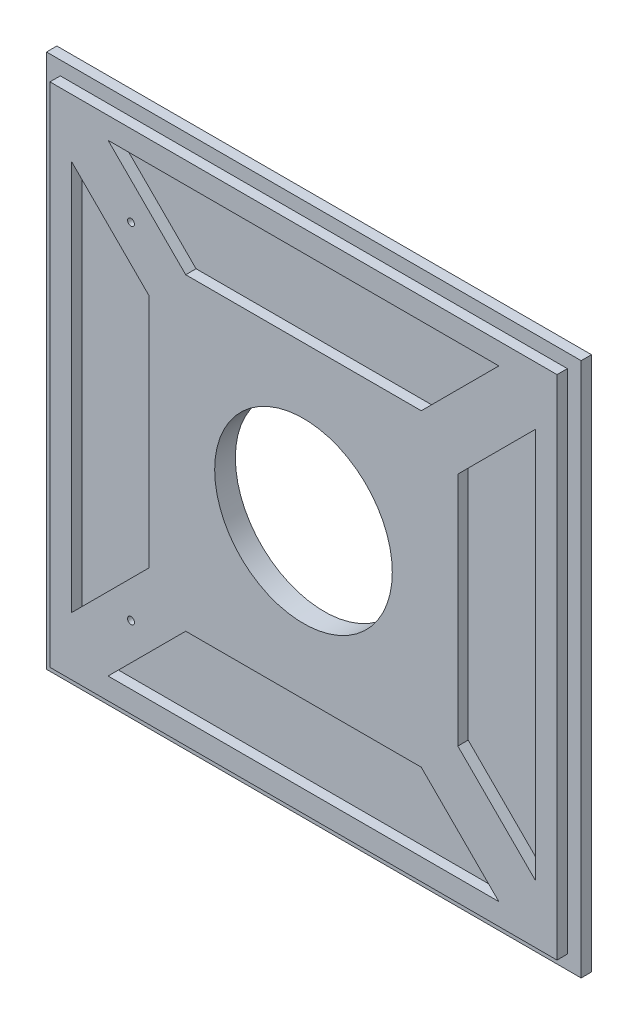
SolidWorks part; units mm, degrees
ref_plane "Front Plane" through (0, 0, 0) normal (0, 0, 1) x (1, 0, 0)
ref_plane "Top Plane" through (0, 0, 0) normal (0, 1, 0) x (1, 0, 0)
ref_plane "Right Plane" through (0, 0, 0) normal (1, 0, 0) x (0, 0, -1)
sketch "Sketch1" plane through (0, 0, 0) normal (0, 0, 1) x (1, 0, 0)
  line L1 (0, 0) -> (310, 0)
  line L2 (0, 0) -> (0, -310)
  line L3 (0, -310) -> (310, -310)
  line L4 (310, 0) -> (310, -310)
  dimension "D1" = 310
  dimension "D2" = 310
extrude "Boss-Extrude1" add sketch "Sketch1" along normal blind 6
sketch "Sketch3" plane through (0, 0, 6) normal (0, 0, 1) x (1, 0, 0)
  line L0 (0, 0) -> (310, -310) construction
  line L1 (302, -8) -> (302, -33)
  line L2 (310, 0) -> (0, -310) construction
  line L3 (302, -8) -> (277, -8)
  line L4 (8, -8) -> (8, -33)
  line L5 (8, -8) -> (33, -8)
  line L6 (8, -302) -> (8, -277)
  line L7 (8, -302) -> (33, -302)
  line L8 (302, -302) -> (277, -302)
  line L9 (302, -302) -> (302, -277)
  line L10 (0, 0) -> (0, -310) construction
  line L11 (268.2868, -20.5) -> (223.2868, -65.5)
  line L13 (20.5, -41.7132) -> (65.5, -86.7132)
  line L15 (41.7132, -289.5) -> (86.7132, -244.5)
  line L17 (289.5, -41.7132) -> (244.5, -86.7132)
  line L19 (33, -8) -> (277, -8)
  line L20 (268.2868, -20.5) -> (41.7132, -20.5)
  line L21 (8, -33) -> (8, -277)
  line L22 (20.5, -41.7132) -> (20.5, -268.2868)
  line L23 (302, -33) -> (302, -277)
  line L24 (289.5, -41.7132) -> (289.5, -268.2868)
  line L25 (33, -302) -> (277, -302)
  line L26 (268.2868, -289.5) -> (41.7132, -289.5)
  line L27 (86.7132, -65.5) -> (223.2868, -65.5)
  line L31 (244.5, -86.7132) -> (244.5, -223.2868)
  line L33 (86.7132, -244.5) -> (223.2868, -244.5)
  line L35 (65.5, -86.7132) -> (65.5, -223.2868)
  line L36 (86.7132, -65.5) -> (41.7132, -20.5)
  line L39 (244.5, -223.2868) -> (289.5, -268.2868)
  line L40 (223.2868, -244.5) -> (268.2868, -289.5)
  line L42 (65.5, -223.2868) -> (20.5, -268.2868)
  line L44 (310, 0) -> (0, 0) construction
  line L45 (310, -310) -> (310, 0) construction
  line L46 (0, -310) -> (310, -310) construction
  point P4 (135, -155)
  point P9 (175, -155)
  point P10 (155, -135)
  point P11 (155, -175)
  point P13 (155, -155)
  dimension "D1" = 25
  dimension "D2" = 25
  dimension "D3" = 25
  dimension "D4" = 25
  dimension "D5" = 25
  dimension "D6" = 25
  dimension "D7" = 25
  dimension "D8" = 25
  dimension "D9" = 8
  dimension "D10" = 45
  dimension "D11" = 12.5
  dimension "D12" = 12.5
  dimension "D13" = 12.5
  dimension "D14" = 12.5
  dimension "D15" = 20
  dimension "D16" = 20
  dimension "D17" = 20
  dimension "D18" = 20
  dimension "D19" = 45
  dimension "D20" = 45
  dimension "D21" = 45
  dimension "D22" = 15
  dimension "D23" = 15
  dimension "D24" = 15
  dimension "D25" = 15
  dimension "D26" = 15
  dimension "D27" = 15
  dimension "D28" = 15
  dimension "D29" = 15
  dimension "D30" = 8
  dimension "D31" = 8
  dimension "D32" = 8
extrude "Boss-Extrude2" add sketch "Sketch3" along normal blind 6
sketch "Sketch4" plane through (0, 0, 12) normal (0, 0, 1) x (1, 0, 0)
  line L0 (0, 0) -> (310, -310) construction
  line L1 (310, 0) -> (0, -310) construction
  circle A0 centre (155, -155) radius 51.5
  dimension "D1" = 103
extrude "Cut-Extrude1" cut sketch "Sketch4" against normal through all
sketch "Sketch10" plane through (0, 0, 0) normal (0, 0, -1) x (-1, 0, 0)
  line L0 (-310, -52.5) -> (0, -52.5)
  line L1 (-310, -310) -> (-310, 0) construction
  line L2 (0, 0) -> (0, -310) construction
  line L3 (-252.5, 0) -> (-252.5, -310)
  line L4 (-310, 0) -> (0, 0) construction
  line L5 (0, -310) -> (-310, -310) construction
  circle A0 centre (-252.5, -52.5) radius 10
  dimension "D3" = 20
  dimension "D1" = 57.5
  dimension "D2" = 52.5
extrude "corner cord hole" [suppressed] cut sketch "Sketch10" against normal through all contours A0
sketch "Sketch11" plane through (0, 0, 0) normal (0, 0, -1) x (-1, 0, 0)
  line L0 (-255, -55) -> (-55, -55) construction
  line L5 (-55, -55) -> (-55, -255) construction
  line L6 (-55, -255) -> (-255, -255) construction
  line L7 (-255, -255) -> (-255, -55) construction
  line L8 (-155, -103.5) -> (-155, -206.5) construction
  line L9 (-206.5, -155) -> (-103.5, -155) construction
  circle A0 centre (-155, -155) radius 51.5 construction
  circle A2 centre (-55, -55) radius 2
  circle A3 centre (-55, -255) radius 2
  point P11 (-155, -155)
  dimension "D6" = 4
  dimension "D7" = 4
  dimension "D1" = 200
  dimension "D2" = 200
  dimension "D3" = 100
  dimension "D4" = 100
extrude "Cut-Extrude5" cut sketch "Sketch11" against normal through all
sketch "Sketch12" plane through (0, 0, 0) normal (0, 0, -1) x (-1, 0, 0)
  line L0 (-339.9534, -155) -> (14.9572, -155) construction
  line L1 (-155, 5.3762) -> (-155, -332.8718) construction
  line L2 (0, 0) -> (0, -310) construction
  line L3 (-310, -310) -> (-310, 0) construction
  line L4 (-310, 0) -> (0, 0) construction
  line L5 (0, -310) -> (-310, -310) construction
  line L6 (-260, -155) -> (-260, -260) construction
  line L7 (-260, -260) -> (-50, -260) construction
  line L8 (-50, -260) -> (-50, -50) construction
  line L9 (-50, -50) -> (-260, -50) construction
  line L10 (-260, -50) -> (-260, -155) construction
  line L11 (-260, -110) -> (-285, -110) construction
  line L12 (-285, -110) -> (-285, -200) construction
  line L13 (-285, -200) -> (-260, -200) construction
  line L15 (-260, -99) -> (-285, -99)
  line L16 (-260, -99) -> (-260, -109)
  line L17 (-260, -109) -> (-285, -109)
  line L18 (-285, -99) -> (-285, -109)
  line L19 (-260, -211) -> (-285, -211)
  line L20 (-260, -211) -> (-260, -201)
  line L21 (-260, -201) -> (-285, -201)
  line L22 (-285, -211) -> (-285, -201)
  dimension "D1" = 105
  dimension "D2" = 105
  dimension "D3" = 210
  dimension "D4" = 210
  dimension "D5" = 25
  dimension "D6" = 105
  dimension "D7" = 90
  dimension "D8" = 60
  dimension "D9" = 1
  dimension "D10" = 1
  dimension "D11" = 10
  dimension "D12" = 10
  dimension "D13" = 25
  dimension "D14" = 25
extrude "Boss-Extrude3" add sketch "Sketch12" along normal blind 6.5
sketch "Sketch13" plane through (0, 0, -6.5) normal (0, 0, -1) x (-1, 0, 0)
  line L1 (-285, -99) -> (-260, -99)
  line L2 (-285, -99) -> (-285, -211)
  line L3 (-285, -211) -> (-260, -211)
  line L4 (-260, -99) -> (-260, -211)
extrude "Boss-Extrude4" add sketch "Sketch13" along normal blind 8
sketch "Sketch14" plane through (0, 0, 12) normal (0, 0, 1) x (1, 0, 0)
  line L0 (310, 0) -> (0, 0) construction
  line L1 (28, -28) -> (282, -28)
  line L2 (28, -28) -> (28, -282)
  line L3 (28, -282) -> (282, -282)
  line L4 (282, -28) -> (282, -282)
  line L6 (310, -310) -> (310, 0) construction
  circle A0 centre (33, -33) radius 1.5
  circle A1 centre (277, -33) radius 1.5
  circle A3 centre (277, -277) radius 1.5
  circle A4 centre (33, -277) radius 1.5
  dimension "D5" = 3
  dimension "D8" = 3
  dimension "D11" = 3
  dimension "D14" = 3
  dimension "D1" = 254
  dimension "D2" = 254
  dimension "D3" = 28
  dimension "D4" = 28
  dimension "D6" = 5
  dimension "D7" = 5
  dimension "D9" = 5
  dimension "D10" = 5
  dimension "D12" = 5
  dimension "D13" = 5
  dimension "D15" = 5
  dimension "D16" = 5
extrude "Cut-Extrude6" [suppressed] cut sketch "Sketch14" against normal through all and the other way through all contours A4 | A1 | A0 | A3
